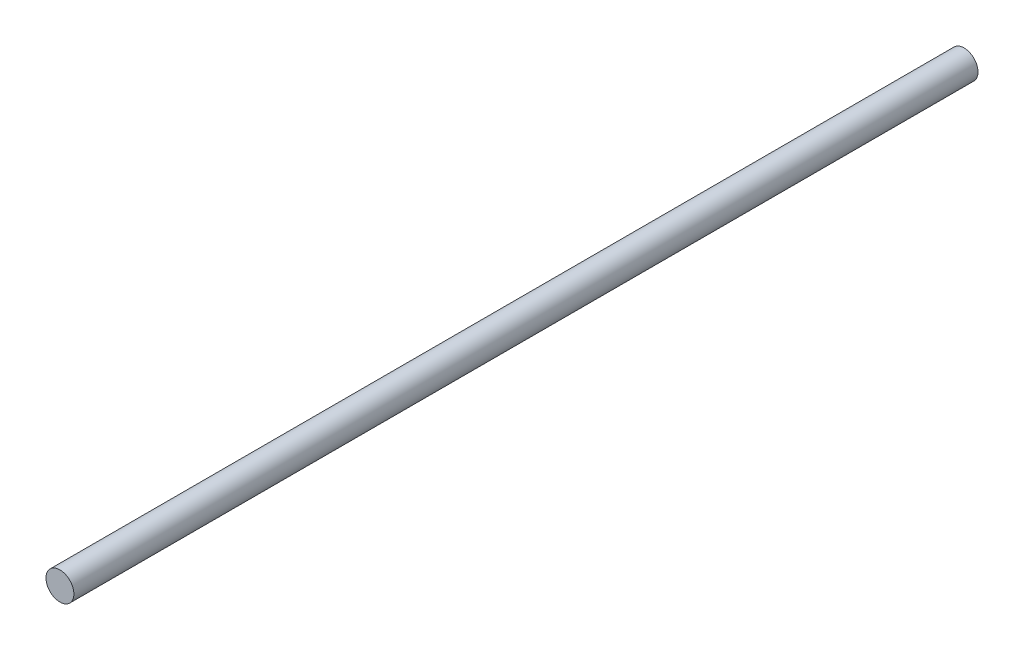
SolidWorks part; units mm, degrees
ref_plane "Front Plane" through (0, 0, 0) normal (0, 0, 1) x (1, 0, 0)
ref_plane "Top Plane" through (0, 0, 0) normal (0, 1, 0) x (1, 0, 0)
ref_plane "Right Plane" through (0, 0, 0) normal (1, 0, 0) x (0, 0, -1)
sketch "Sketch1" plane through (0, 0, 0) normal (0, 0, 1) x (1, 0, 0)
  circle A0 centre (0, 0) radius 5
  dimension "D1" = 10
extrude "Boss-Extrude1" add sketch "Sketch1" along normal blind 324 from offset 1
